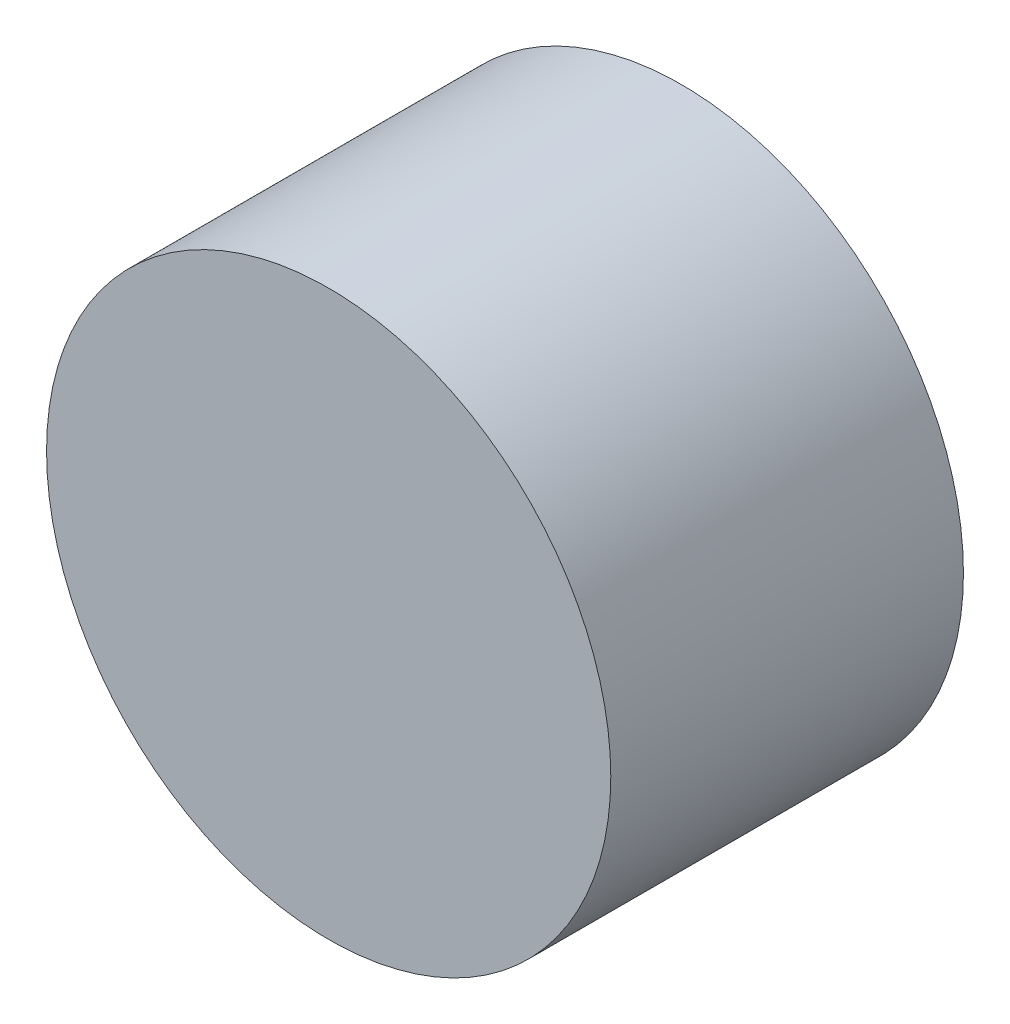
SolidWorks part; units mm, degrees
ref_plane "前视基准面" through (0, 0, 0) normal (0, 0, 1) x (1, 0, 0)
ref_plane "上视基准面" through (0, 0, 0) normal (0, 1, 0) x (1, 0, 0)
ref_plane "右视基准面" through (0, 0, 0) normal (1, 0, 0) x (0, 0, -1)
sketch "草图1" plane through (0, 0, 0) normal (0, 0, 1) x (1, 0, 0)
  circle A0 centre (0, 0) radius 4
  dimension "D1" = 8
extrude "凸台-拉伸1" add sketch "草图1" along normal blind 5
